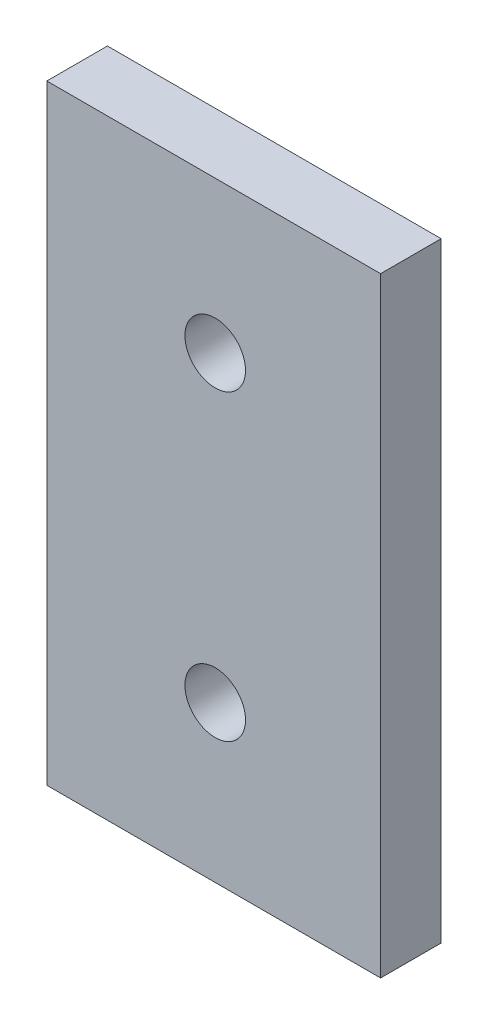
SolidWorks part; units mm, degrees
ref_plane "Front Plane" through (0, 0, 0) normal (0, 0, 1) x (1, 0, 0)
ref_plane "Top Plane" through (0, 0, 0) normal (0, 1, 0) x (1, 0, 0)
ref_plane "Right Plane" through (0, 0, 0) normal (1, 0, 0) x (0, 0, -1)
sketch "Sketch1" plane through (0, 0, 0) normal (0, 0, 1) x (1, 0, 0)
  line L0 (0, 20.1451) -> (11.0216, 20.1451)
  line L1 (11.0216, 20.1451) -> (11.0216, 0)
  line L2 (0, 20.1451) -> (0, 0)
  line L3 (0, 0) -> (11.0216, 0)
  circle A0 centre (5.56, 15.1451) radius 1
  circle A1 centre (5.56, 5.1451) radius 1
  dimension "D1" = 2
  dimension "D2" = 5.56
  dimension "D3" = 11.0216
  dimension "D5" = 5.1451
  dimension "D6" = 15.1451
  dimension "D8" = 20.1451
extrude "Boss-Extrude1" add sketch "Sketch1" along normal blind 2
